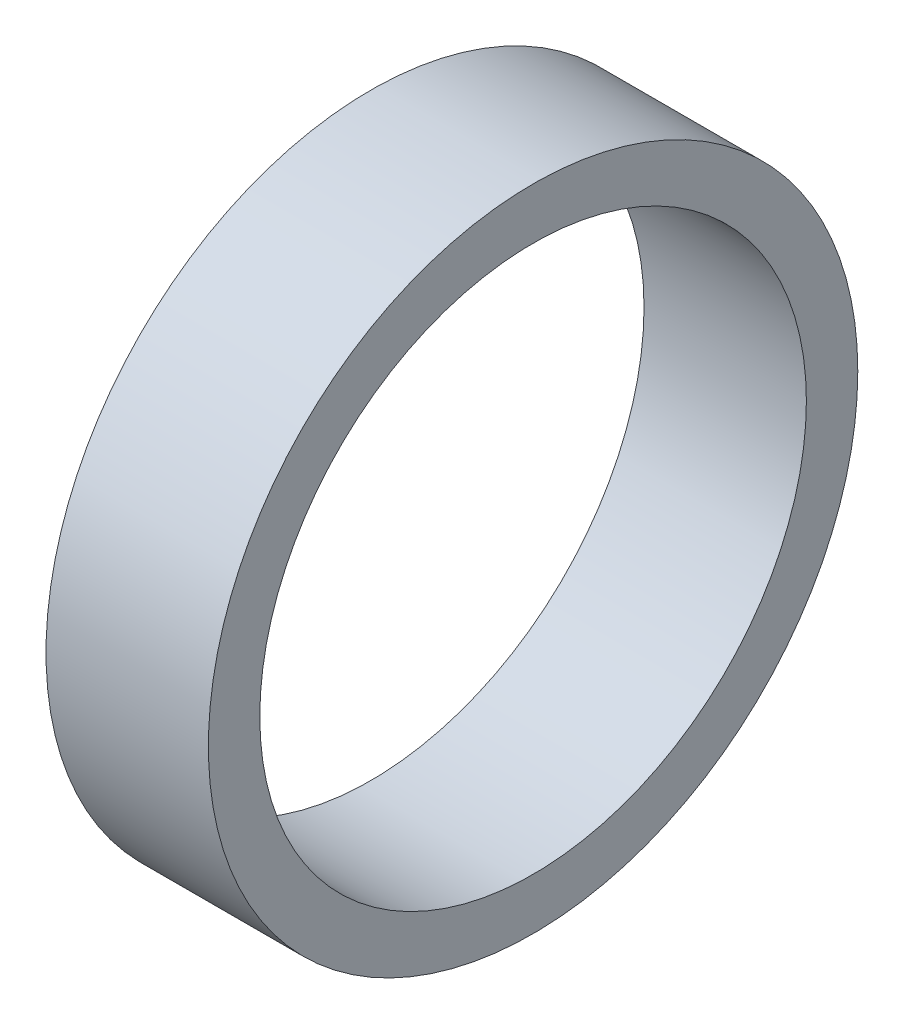
SolidWorks part; units mm, degrees
ref_plane "Front Plane" through (0, 0, 0) normal (0, 0, 1) x (1, 0, 0)
ref_plane "Top Plane" through (0, 0, 0) normal (0, 1, 0) x (1, 0, 0)
ref_plane "Right Plane" through (0, 0, 0) normal (1, 0, 0) x (0, 0, -1)
sketch "Sketch1" plane through (0, 0, 0) normal (1, 0, 0) x (0, 0, -1)
  circle A0 centre (0, 0) radius 50.5
  circle A1 centre (0, 0) radius 60
  dimension "D1" = 101
  dimension "D2" = 120
extrude "Boss-Extrude1" add sketch "Sketch1" along normal blind 30
